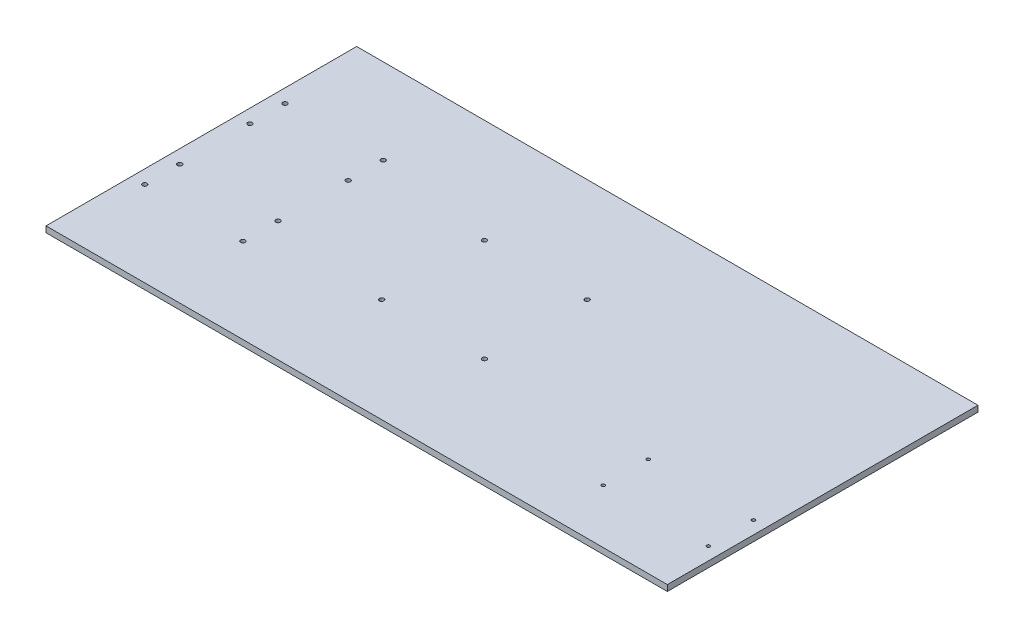
SolidWorks part; units mm, degrees
ref_plane "前视基准面" through (0, 0, 0) normal (0, 0, 1) x (1, 0, 0)
ref_plane "上视基准面" through (0, 0, 0) normal (0, 1, 0) x (1, 0, 0)
ref_plane "右视基准面" through (0, 0, 0) normal (1, 0, 0) x (0, 0, -1)
sketch "草图1" plane through (0, 0, 0) normal (0, 1, 0) x (1, 0, 0)
  line L13 (-565, 310) -> (675, 310)
  line L14 (-565, 310) -> (-565, -310)
  line L15 (-565, -310) -> (675, -310)
  line L16 (675, 310) -> (675, -310)
  point P0 (0, 0)
  dimension "D1" = 675
  dimension "D2" = 1240
  dimension "D3" = 310
  dimension "D4" = 620
extrude "凸台-拉伸1" add sketch "草图1" along normal blind 12
sketch "草图2" plane through (0, 0, 0) normal (0, 1, 0) x (1, 0, 0)
  circle A4 centre (-538, 140) radius 4.5
  circle A5 centre (-538, 70) radius 4.5
  circle A6 centre (-538, -70) radius 4.5
  circle A7 centre (-538, -140) radius 4.5
  circle A8 centre (-342, 140) radius 4.5
  circle A9 centre (-342, 70) radius 4.5
  circle A10 centre (-342, -70) radius 4.5
  circle A11 centre (-342, -140) radius 4.5
  point P0 (0, 0)
  dimension "D1" = 9
  dimension "D2" = 9
  dimension "D3" = 9
  dimension "D4" = 9
  dimension "D5" = 9
  dimension "D6" = 9
  dimension "D7" = 9
  dimension "D8" = 9
  dimension "D9" = 196
  dimension "D10" = 70
  dimension "D11" = 210
  dimension "D12" = 280
  dimension "D13" = 538
  dimension "D14" = 140
extrude "Hopper Frame Holes" cut sketch "草图2" against normal mid plane 12 from offset 6
sketch "草图3" plane through (0, 0, 0) normal (0, 1, 0) x (1, 0, 0)
  circle A0 centre (102.5305, 102.5305) radius 4.5
  circle A1 centre (-102.5305, 102.5305) radius 4.5
  circle A2 centre (-102.5305, -102.5305) radius 4.5
  circle A3 centre (102.5305, -102.5305) radius 4.5
extrude "Drive Mounting Holes" cut sketch "草图3" against normal mid plane 28 from offset 6
sketch "Holder Mounting Holes Layout" plane through (0, 0, 0) normal (0, 1, 0) x (1, 0, 0)
  circle A0 centre (439.4, -202.5131) radius 3.3
  circle A1 centre (649.4, -202.5131) radius 3.3
  circle A2 centre (439.4, -112.5131) radius 3.3
  circle A3 centre (649.4, -112.5131) radius 3.3
  point P8 (0, 0)
  dimension "D1" = 6.6
  dimension "D2" = 6.6
  dimension "D3" = 6.6
  dimension "D4" = 6.6
  dimension "D5" = 439.4
  dimension "D6" = 649.4
  dimension "D7" = 90
  dimension "D8" = 202.5131
extrude "Holder Mounting Holes" cut sketch "Holder Mounting Holes Layout" against normal mid plane 12 from offset 6
